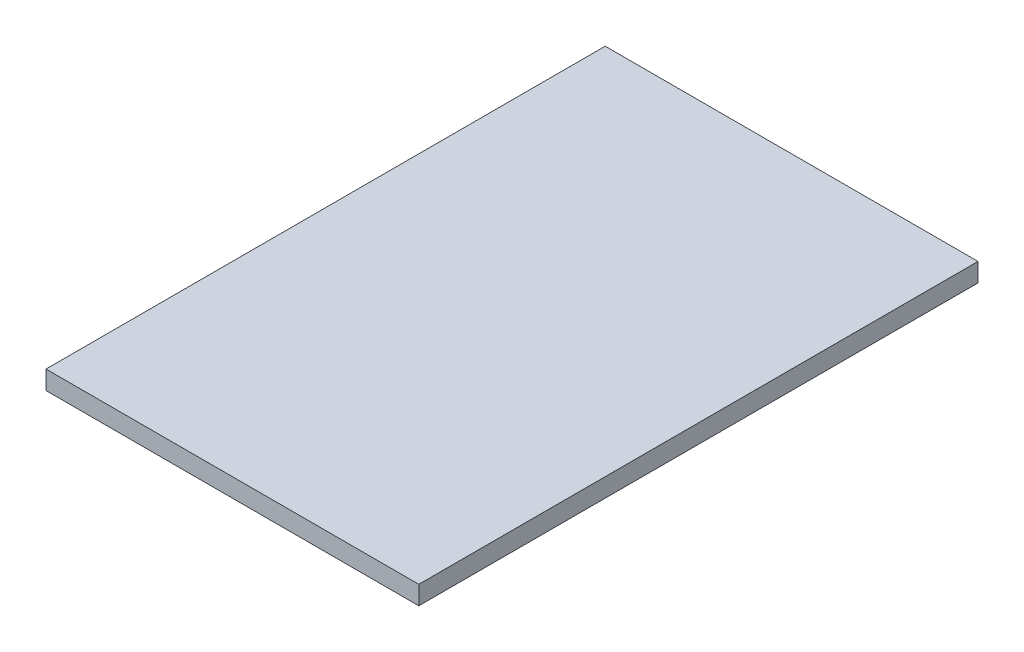
SolidWorks part; units mm, degrees
ref_plane "Plano frontal" through (0, 0, 0) normal (0, 0, 1) x (1, 0, 0)
ref_plane "Plano superior" through (0, 0, 0) normal (0, 1, 0) x (1, 0, 0)
ref_plane "Plano direito" through (0, 0, 0) normal (1, 0, 0) x (0, 0, -1)
sketch "Esboço1" plane through (0, 0, 0) normal (0, 1, 0) x (1, 0, 0)
  line L0 (-304.5911, 0) -> (14924.964, 0) construction
  line L1 (0, -304.5911) -> (0, 14924.964) construction
  line L2 (-10, 15) -> (-10, -15)
  line L3 (-10, 15) -> (10, 15)
  line L4 (-10, -15) -> (10, -15)
  line L5 (10, 15) -> (10, -15)
  point P10 (0, -15)
  point P11 (0, 15)
  dimension "D1" = 30
  dimension "D2" = 10
extrude "Ressalto-extrusão1" add sketch "Esboço1" along normal blind 1
